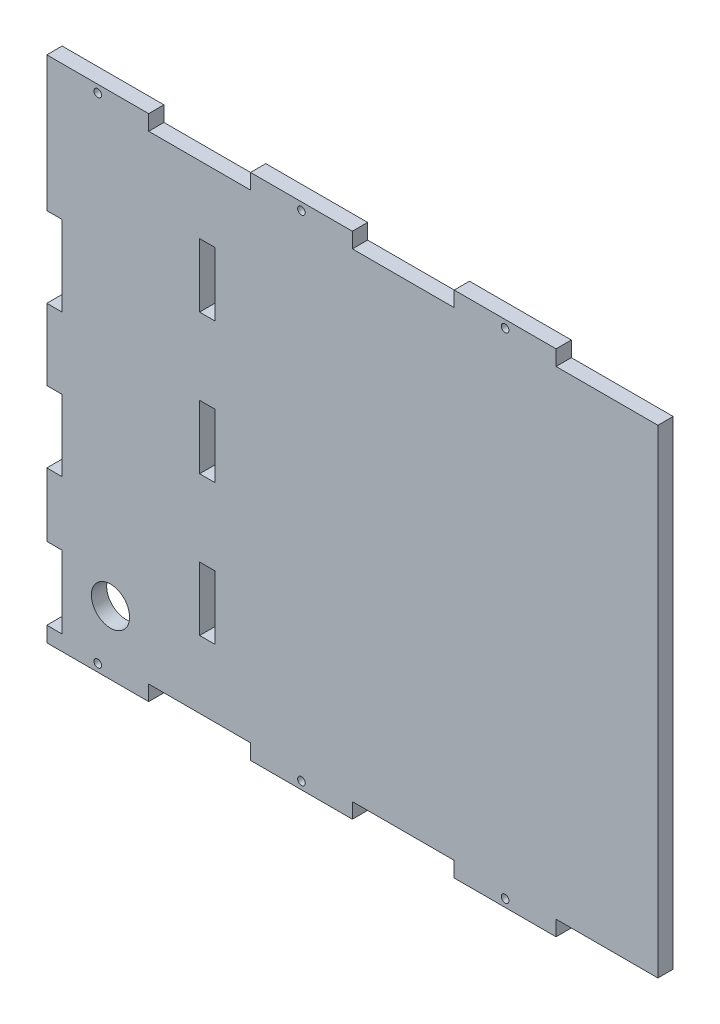
SolidWorks part; units mm, degrees
ref_plane "Plan de face" through (0, 0, 0) normal (0, 0, 1) x (1, 0, 0)
ref_plane "Plan de dessus" through (0, 0, 0) normal (0, 1, 0) x (1, 0, 0)
ref_plane "Plan de droite" through (0, 0, 0) normal (1, 0, 0) x (0, 0, -1)
sketch "Esquisse1" plane through (0, 0, 0) normal (0, 0, 1) x (1, 0, 0)
  line L1 (135, -100) -> (-135, -100)
  line L2 (135, -100) -> (135, 100)
  line L3 (135, 100) -> (-135, 100)
  line L4 (-135, -100) -> (-135, 100)
  line L5 (135, -100) -> (-135, 100) construction
  line L6 (135, 100) -> (-135, -100) construction
  point P0 (0, 0)
extrude "Boss.-Extru.1" add sketch "Esquisse1" along normal blind 6
sketch "Esquisse2" plane through (0, 0, 0) normal (0, 0, -1) x (-1, 0, 0)
  line L1 (135, 100) -> (135, -100) construction
  line L2 (135, -100) -> (-135, -100) construction
  circle A0 centre (110, -75) radius 7.5
  dimension "D1" = 25
  dimension "D3" = 15
  dimension "D2" = 25
extrude "Enlèv. mat.-Extru.1" cut sketch "Esquisse2" against normal blind 10
sketch "Esquisse4" plane through (0, 0, 6) normal (0, 0, 1) x (1, 0, 0)
  line L0 (-135, -100) -> (135, -100) construction
  line L1 (-95, -100) -> (-55, -100)
  line L2 (-95, -100) -> (-95, -94)
  line L3 (-95, -94) -> (-55, -94)
  line L4 (-55, -100) -> (-55, -94)
  line L5 (135, 100) -> (-135, 100) construction
  line L6 (-15, -100) -> (25, -100)
  line L7 (-15, -100) -> (-15, -94)
  line L8 (-15, -94) -> (25, -94)
  line L9 (25, -100) -> (25, -94)
  line L10 (65, -100) -> (105, -100)
  line L11 (65, -100) -> (65, -94)
  line L12 (65, -94) -> (105, -94)
  line L13 (105, -100) -> (105, -94)
  line L14 (-95, 100) -> (-55, 100)
  line L15 (-95, 100) -> (-95, 94)
  line L16 (-95, 94) -> (-55, 94)
  line L17 (-55, 100) -> (-55, 94)
  line L18 (-135, 100) -> (-135, -100) construction
  line L19 (-15, 100) -> (25, 100)
  line L20 (-15, 100) -> (-15, 94)
  line L21 (-15, 94) -> (25, 94)
  line L22 (25, 100) -> (25, 94)
  line L23 (65, 100) -> (105, 100)
  line L24 (65, 100) -> (65, 94)
  line L25 (65, 94) -> (105, 94)
  line L26 (105, 100) -> (105, 94)
  line L28 (135, -100) -> (135, 100) construction
  line L29 (135, -100) -> (129, -100)
  line L30 (135, -100) -> (135, -50)
  line L31 (135, -50) -> (129, -50)
  line L32 (129, -100) -> (129, -50)
  line L33 (135, 100) -> (129, 100)
  line L34 (135, 100) -> (135, 50)
  line L35 (135, 50) -> (129, 50)
  line L36 (129, 100) -> (129, 50)
  line L37 (135, -20) -> (129, -20)
  line L38 (135, -20) -> (135, 20)
  line L39 (135, 20) -> (129, 20)
  line L40 (129, -20) -> (129, 20)
  dimension "D1" = 6
  dimension "D2" = 6
  dimension "D3" = 6
  dimension "D4" = 40
  dimension "D5" = 40
  dimension "D6" = 40
  dimension "D7" = 40
  dimension "D8" = 40
  dimension "D9" = 40
  dimension "D10" = 6
  dimension "D11" = 40
  dimension "D12" = 40
  dimension "D13" = 6
  dimension "D14" = 40
  dimension "D15" = 6
  dimension "D16" = 40
  dimension "D17" = 40
  dimension "D18" = 40
  dimension "D19" = 30
  dimension "D20" = 30
  dimension "D21" = 50
  dimension "D22" = 50
  dimension "D23" = 6
  dimension "D24" = 6
  dimension "D25" = 6
extrude "Enlèv. mat.-Extru.2" cut sketch "Esquisse4" against normal blind 6
sketch "Esquisse5" plane through (0, 0, 0) normal (0, 0, -1) x (-1, 0, 0)
  line L0 (135, 100) -> (135, -100) construction
  line L1 (69, -42.5) -> (75, -42.5)
  line L2 (69, -42.5) -> (69, -67.5)
  line L3 (69, -67.5) -> (75, -67.5)
  line L4 (75, -42.5) -> (75, -67.5)
  line L5 (69, 12.5) -> (75, 12.5)
  line L6 (69, 12.5) -> (69, -12.5)
  line L7 (69, -12.5) -> (75, -12.5)
  line L8 (75, 12.5) -> (75, -12.5)
  line L9 (69, 67.5) -> (75, 67.5)
  line L10 (69, 67.5) -> (69, 42.5)
  line L11 (69, 42.5) -> (75, 42.5)
  line L12 (75, 67.5) -> (75, 42.5)
  line L13 (55, -100) -> (15, -100) construction
  point P15 (135, 0)
  dimension "D1" = 25
  dimension "D2" = 6
  dimension "D3" = 32.5
  dimension "D4" = 30
  dimension "D5" = 25
  dimension "D6" = 25
  dimension "D7" = 30
  dimension "D8" = 60
  dimension "D9" = 60
  dimension "D10" = 60
  dimension "D11" = 6
  dimension "D12" = 6
extrude "Enlèv. mat.-Extru.3" cut sketch "Esquisse5" against normal blind 10
sketch "Esquisse6" plane through (0, 0, 6) normal (0, 0, 1) x (1, 0, 0)
  line L1 (105, 100) -> (135.1793, 100)
  line L2 (105, 100) -> (105, -100.522)
  line L3 (105, -100.522) -> (135.1793, -100.522)
  line L4 (135.1793, 100) -> (135.1793, -100.522)
extrude "Enlèv. mat.-Extru.4" cut sketch "Esquisse6" against normal through all
sketch "Esquisse7" plane through (0, 0, 0) normal (0, 0, -1) x (-1, 0, 0)
  line L0 (-65, 100) -> (-25, 100) construction
  line L1 (-25, -100) -> (-65, -100) construction
  line L2 (55, -100) -> (15, -100) construction
  line L3 (135, -100) -> (95, -100) construction
  line L4 (-65, 100) -> (-65, 94) construction
  line L5 (15, 100) -> (15, 94) construction
  line L6 (-25, -100) -> (-25, -94) construction
  line L7 (55, -100) -> (55, -94) construction
  line L8 (95, -94) -> (95, -100) construction
  line L9 (95, 100) -> (95, 94) construction
  circle A0 centre (-45, 97) radius 2.995
  circle A1 centre (35, 97) radius 2.995
  circle A2 centre (115, 97) radius 2.995
  circle A3 centre (-45, -97) radius 2.995
  circle A4 centre (35, -97) radius 2.995
  circle A5 centre (115, -97) radius 2.995
  dimension "D1" = 5.99
  dimension "D3" = 5.99
  dimension "D4" = 5.99
  dimension "D5" = 5.99
  dimension "D6" = 5.99
  dimension "D7" = 5.99
  dimension "D2" = 3
  dimension "D8" = 3
  dimension "D9" = 3
  dimension "D10" = 3
  dimension "D11" = 20
  dimension "D12" = 20
  dimension "D13" = 20
  dimension "D14" = 20
  dimension "D15" = 20
  dimension "D16" = 20
extrude "Enlèv. mat.-Extru.5" cut sketch "Esquisse7" against normal blind 3
sketch "Esquisse8" plane through (0, 0, 0) normal (0, 0, -1) x (-1, 0, 0)
  circle A0 centre (-45, 97) radius 1.5
  circle A1 centre (35, 97) radius 1.5
  circle A2 centre (115, 97) radius 1.5
  circle A3 centre (-45, -97) radius 1.5
  circle A4 centre (35, -97) radius 1.5
  circle A5 centre (115, -97) radius 1.5
extrude "Enlèv. mat.-Extru.6" cut sketch "Esquisse8" against normal blind 13
sketch "Esquisse9" plane through (0, 0, 0) normal (0, 0, -1) x (-1, 0, 0)
  line L0 (135, 100) -> (135, -100) construction
  line L1 (135, -94) -> (129, -94)
  line L2 (135, -94) -> (135, -65.5)
  line L3 (135, -65.5) -> (129, -65.5)
  line L4 (129, -94) -> (129, -65.5)
  line L5 (135, -100) -> (95, -100) construction
  line L7 (135, -40.5) -> (129, -40.5)
  line L8 (135, -40.5) -> (135, -12.5)
  line L9 (135, -12.5) -> (129, -12.5)
  line L10 (129, -40.5) -> (129, -12.5)
  line L11 (135, 15.5) -> (129, 15.5)
  line L12 (135, 15.5) -> (135, 47)
  line L13 (135, 47) -> (129, 47)
  line L14 (129, 15.5) -> (129, 47)
  dimension "D1" = 6
  dimension "D2" = 6
  dimension "D3" = 28.5
  dimension "D4" = 25
  dimension "D5" = 28
  dimension "D6" = 28
  dimension "D7" = 31.5
extrude "Enlèv. mat.-Extru.7" cut sketch "Esquisse9" against normal blind 10
